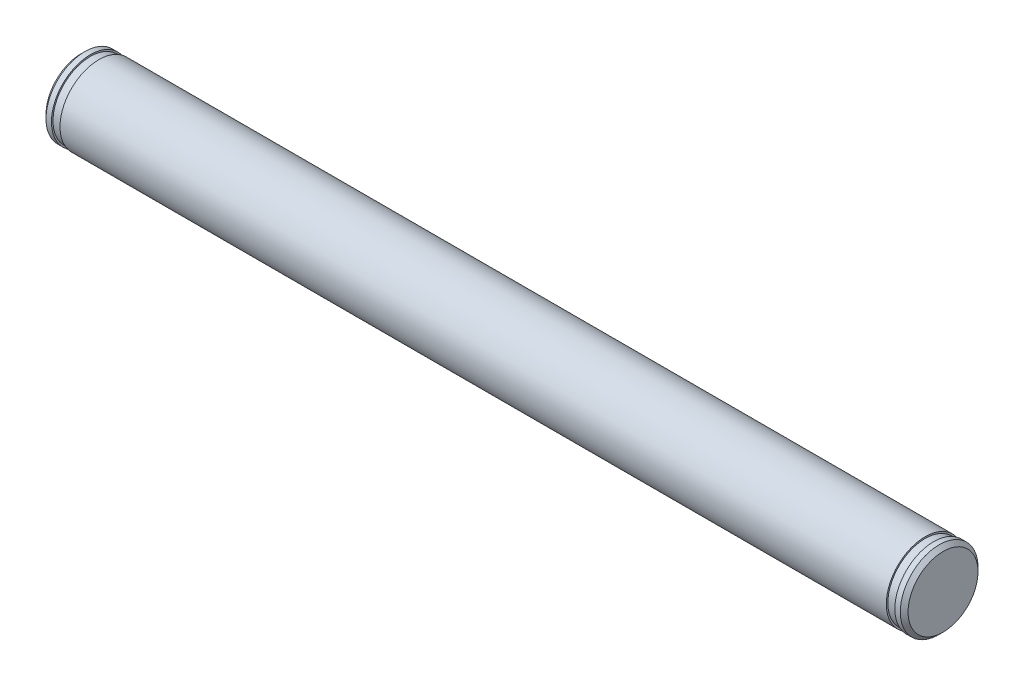
SolidWorks part; units mm, degrees
ref_plane "前视基准面" through (0, 0, 0) normal (0, 0, 1) x (1, 0, 0)
ref_plane "上视基准面" through (0, 0, 0) normal (0, 1, 0) x (1, 0, 0)
ref_plane "右视基准面" through (0, 0, 0) normal (1, 0, 0) x (0, 0, -1)
other "Configuration Table"
sketch "草图1" plane through (0, 0, 0) normal (0, 0, 1) x (1, 0, 0)
  line L0 (-55.45, 0) -> (55.45, 0) construction
  line L1 (55.45, 0) -> (55.45, 5)
  line L2 (55.45, 5) -> (54.25, 5)
  line L3 (54.25, 5) -> (54.25, 4.8)
  line L4 (54.25, 4.8) -> (53.15, 4.8)
  line L5 (53.15, 4.8) -> (53.15, 5)
  line L6 (53.15, 5) -> (-53.15, 5)
  line L7 (0, 5) -> (0, 0) construction
  line L8 (53.25, 4.8) -> (53.25, 0) construction
  line L9 (-55.45, 0) -> (-55.45, 5)
  line L10 (-53.25, 4.8) -> (-53.25, 0) construction
  line L11 (-53.15, 4.8) -> (-53.15, 5)
  line L12 (-54.25, 4.8) -> (-53.15, 4.8)
  line L13 (-54.25, 5) -> (-54.25, 4.8)
  line L14 (-55.45, 5) -> (-54.25, 5)
  line L15 (55.45, 0) -> (-55.45, 0)
  dimension "D1" = 1.1
  dimension "D2" = 1
  dimension "D3" = 10
  dimension "D4" = 9.6
  dimension "D5" = 1.2
  dimension "D6" = 106.5
revolve "旋转1" add sketch "草图1" angle 360 about L15
chamfer "倒角1" distance 0.5 angle 45 2 edges at (55.45, 5, 0) (-55.45, 5, 0)
ref_plane "基准面1" through (53.25, 0, 0) normal (1, 0, 0) x (0, 0, -1)
ref_plane "基准面2" through (-53.25, 0, 0) normal (-1, 0, 0) x (0, 0, 1)
